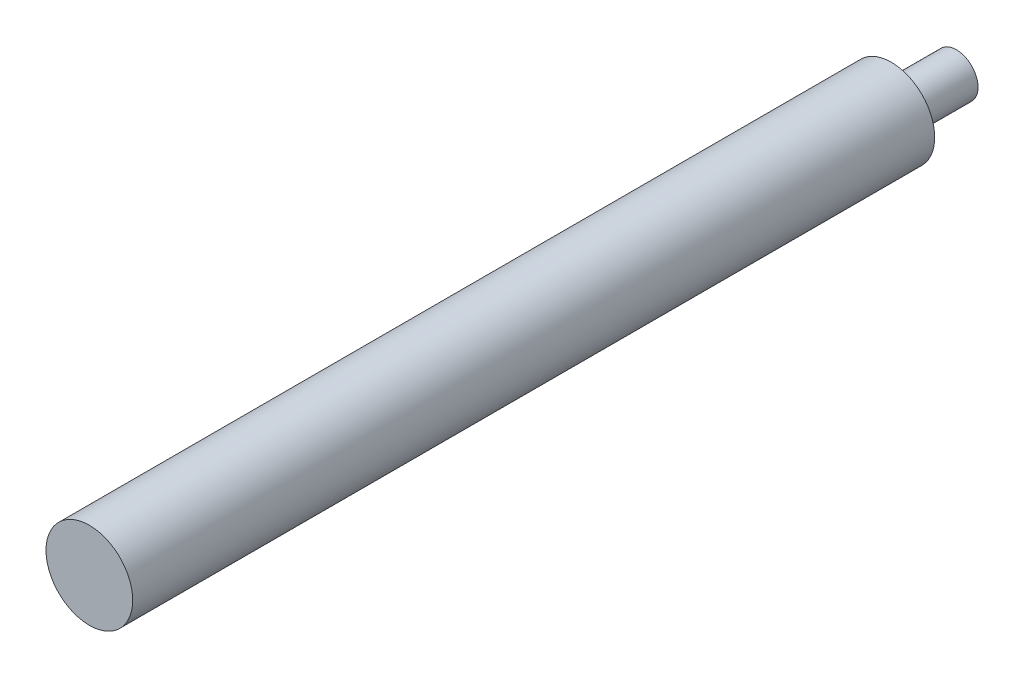
SolidWorks part; units mm, degrees
ref_plane "前视基准面" through (0, 0, 0) normal (0, 0, 1) x (1, 0, 0)
ref_plane "上视基准面" through (0, 0, 0) normal (0, 1, 0) x (1, 0, 0)
ref_plane "右视基准面" through (0, 0, 0) normal (1, 0, 0) x (0, 0, -1)
sketch "草图1" plane through (0, 0, 0) normal (0, 0, 1) x (1, 0, 0)
  circle A0 centre (0, 0) radius 10
extrude "凸台-拉伸1" add sketch "草图1" along normal blind 200
sketch "草图2" plane through (0, 0, 0) normal (0, 1, 0) x (1, 0, 0)
  line L0 (0, 0) -> (0, -38) construction
  line L1 (0, -38) -> (14.3238, -38)
  line L2 (14.3238, -38) -> (14.3238, -48)
  line L3 (14.3238, -48) -> (0, -48)
  line L4 (0, -38) -> (0, -48)
  dimension "D1" = 38
  dimension "D5" = 10
sketch "草图3" plane through (0, 0, 0) normal (0, 0, -1) x (-1, 0, 0)
  circle A0 centre (0, 0) radius 5
  circle A1 centre (0, 0) radius 10.8926
extrude "切除-拉伸1" cut sketch "草图3" against normal blind 15
